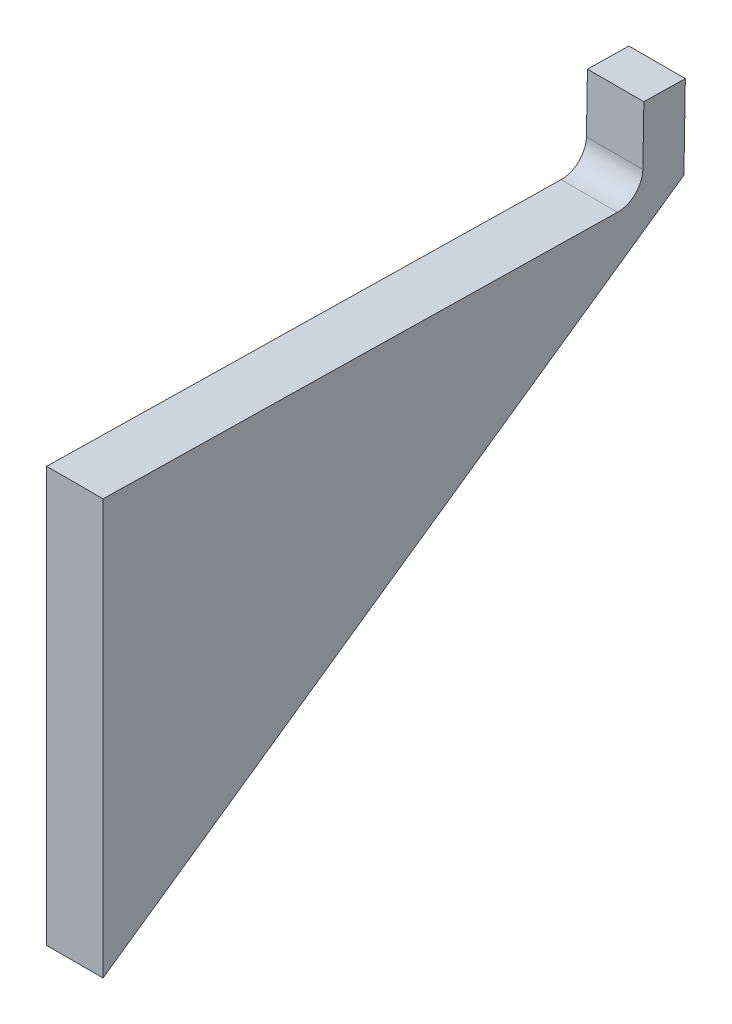
SolidWorks part; units mm, degrees
material "Polietileno reticulado"
ref_plane "Alzado" through (0, 0, 0) normal (0, 0, 1) x (1, 0, 0)
ref_plane "Planta" through (0, 0, 0) normal (0, 1, 0) x (1, 0, 0)
ref_plane "Vista lateral" through (0, 0, 0) normal (1, 0, 0) x (0, 0, -1)
sketch "Croquis1" plane through (0, 0, 0) normal (1, 0, 0) x (0, 0, -1)
  line L12 (0, 0) -> (74.2717, 0) construction
  line L13 (65.0425, 1.8651) -> (65.1646, 8.8641)
  line L14 (65.1646, 8.8641) -> (70.1639, 8.7768)
  line L15 (69.9893, -1.2217) -> (0, -50)
  line L17 (0, 0) -> (99.4694, -1.7362) construction
  line L18 (69.9893, -1.2217) -> (70.1639, 8.7768)
  line L20 (0, -50) -> (0, 0)
  line L21 (61.9906, -1.082) -> (0, 0)
  arc A0 (65.0425, 1.8651) -> (61.9906, -1.082) centre (62.0429, 1.9175) cw
  point P12 (64.9901, -1.1344)
  dimension "D5" = 3
  dimension "D1" = 65
  dimension "D2" = 50
  dimension "D3" = 5
  dimension "D4" = 10
  dimension "D7" = 1
extrude "Saliente-Extruir1" add sketch "Croquis1" along normal blind 6.8
ref_plane "Plano1" through (3.4, 0, 0) normal (1, 0, 0) x (0, 0, -1)
